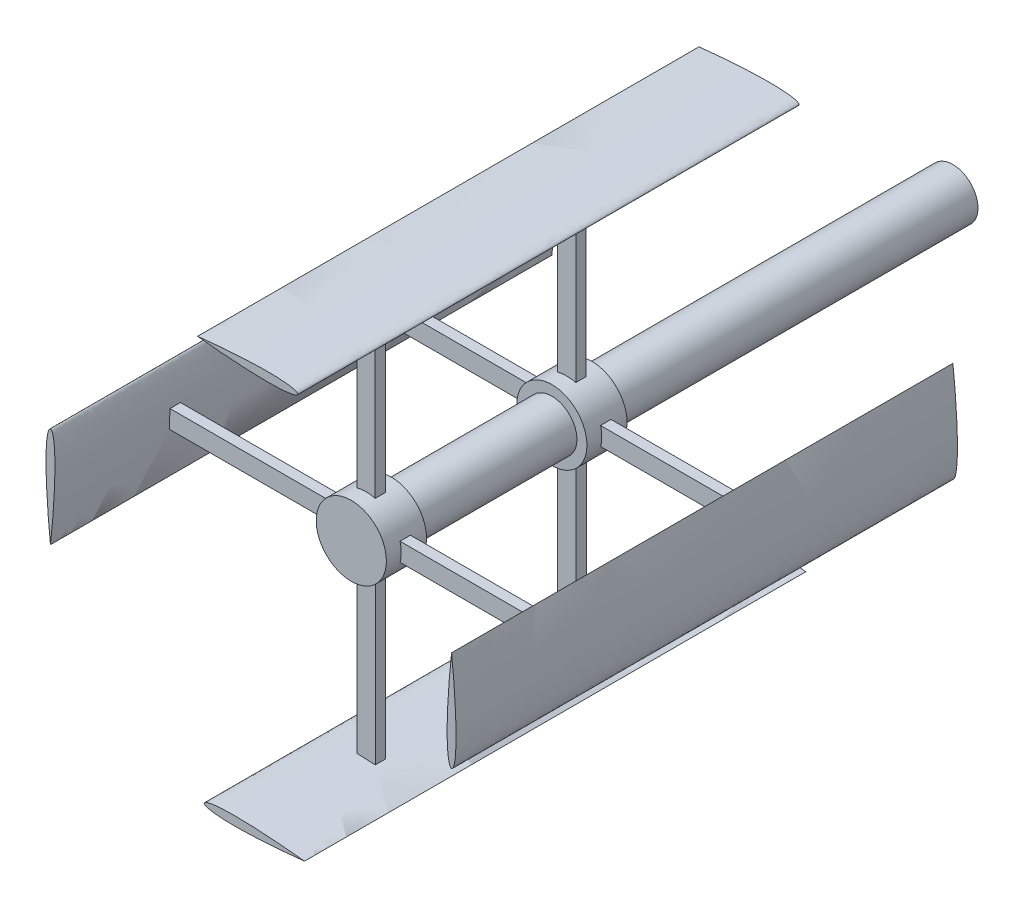
SolidWorks part; units mm, degrees
ref_plane "Front Plane" through (0, 0, 0) normal (0, 0, 1) x (1, 0, 0)
ref_plane "Top Plane" through (0, 0, 0) normal (0, 1, 0) x (1, 0, 0)
ref_plane "Right Plane" through (0, 0, 0) normal (1, 0, 0) x (0, 0, -1)
curve "Curve1"
  spline degree 3 poles (990.8652, -0.9511, 0) (1002.2959, 0, 0) (990.8652, 0.9511, 0) (981.4966, 2.5372, 0) (958.7395, 4.9688, 0) (930.7792, 7.9871, 0) (894.3471, 11.5291, 0) (851.5737, 15.4379, 0) (802.6464, 19.638, 0) (748.5888, 24.0066, 0) (690.2628, 28.3691, 0) (628.6855, 32.5963, 0) (564.9061, 36.4936, 0) (500.0164, 39.8961, 0) (435.1246, 42.6014, 0) (381.5433, 44.1643, 0) (339.5117, 44.8822, 0) (308.9339, 45.137, 0) (279.1721, 45.1014, 0) (250.3536, 44.7183, 0) (222.6042, 44.0458, 0) (196.0449, 43.0302, 0) (170.7873, 41.7085, 0) (146.9363, 40.0498, 0) (124.593, 38.0822, 0) (103.8602, 35.7885, 0) (84.8245, 33.2124, 0) (67.5602, 30.4204, 0) (52.1393, 27.4249, 0) (38.6118, 24.2363, 0) (27.0418, 20.7473, 0) (17.4544, 16.8931, 0) (9.9374, 12.6406, 0) (4.5317, 8.2, 0) (1.1558, 4.1301, 0) (-0.473, 0, 0) (1.1558, -4.1301, 0) (4.5317, -8.2, 0) (9.9374, -12.6406, 0) (17.4544, -16.8931, 0) (27.0418, -20.7473, 0) (38.6118, -24.2363, 0) (52.1393, -27.4249, 0) (67.5602, -30.4204, 0) (84.8245, -33.2124, 0) (103.8602, -35.7885, 0) (124.593, -38.0822, 0) (146.9363, -40.0498, 0) (170.7873, -41.7085, 0) (196.0449, -43.0302, 0) (222.6042, -44.0458, 0) (250.3536, -44.7183, 0) (279.1721, -45.1014, 0) (308.9339, -45.137, 0) (339.5117, -44.8822, 0) (381.5433, -44.1643, 0) (435.1246, -42.6014, 0) (500.0164, -39.8961, 0) (564.9061, -36.4936, 0) (628.6855, -32.5963, 0) (690.2628, -28.3691, 0) (748.5888, -24.0066, 0) (802.6464, -19.638, 0) (851.5737, -15.4379, 0) (894.3471, -11.5291, 0) (930.7792, -7.9871, 0) (958.7395, -4.9688, 0) (981.4966, -2.5372, 0) (990.8652, -0.9511, 0) (1002.2959, 0, 0) (990.8652, 0.9511, 0) knots -0.018944 -0.008488 -0.002133 0 0.002133 0.008488 0.018944 0.033319 0.051356 0.072756 0.097141 0.124097 0.153163 0.183834 0.215589 0.247878 0.280151 0.31186 0.327333 0.342463 0.357187 0.371448 0.385183 0.398331 0.410845 0.422673 0.433769 0.44409 0.453589 0.46224 0.47001 0.476871 0.482833 0.487909 0.492155 0.495592 0.498196 0.5 0.501804 0.504408 0.507845 0.512091 0.517167 0.523129 0.52999 0.53776 0.546411 0.55591 0.566231 0.577327 0.589155 0.601669 0.614817 0.628552 0.642813 0.657537 0.672667 0.68814 0.719849 0.752122 0.784411 0.816166 0.846837 0.875903 0.902859 0.927244 0.948644 0.966681 0.981056 0.991512 0.997867 1 1.002133 1.008488 1.018944 periodic
sketch "Sketch2" plane through (0, 0, 0) normal (0, 0, 1) x (1, 0, 0)
  line L0 (0, 0) -> (1000, 0)
  circle A0 centre (466.8967, 2000) radius 2000
  spline S0 degree 3 poles (990.8652, -0.9511) (1002.2959, 0) (990.8652, 0.9511) (981.4966, 2.5372) (958.7395, 4.9688) (930.7792, 7.9871) (894.3471, 11.5291) (851.5737, 15.4379) (802.6464, 19.638) (748.5888, 24.0066) (690.2628, 28.3691) (628.6855, 32.5963) (564.9061, 36.4936) (500.0164, 39.8961) (435.1246, 42.6014) (381.5433, 44.1643) (339.5117, 44.8822) (308.9339, 45.137) (279.1721, 45.1014) (250.3536, 44.7183) (222.6042, 44.0458) (196.0449, 43.0302) (170.7873, 41.7085) (146.9363, 40.0498) (124.593, 38.0822) (103.8602, 35.7885) (84.8245, 33.2124) (67.5602, 30.4204) (52.1393, 27.4249) (38.6118, 24.2363) (27.0418, 20.7473) (17.4544, 16.8931) (9.9374, 12.6406) (4.5317, 8.2) (1.1558, 4.1301) (-0.473, 0) (1.1558, -4.1301) (4.5317, -8.2) (9.9374, -12.6406) (17.4544, -16.8931) (27.0418, -20.7473) (38.6118, -24.2363) (52.1393, -27.4249) (67.5602, -30.4204) (84.8245, -33.2124) (103.8602, -35.7885) (124.593, -38.0822) (146.9363, -40.0498) (170.7873, -41.7085) (196.0449, -43.0302) (222.6042, -44.0458) (250.3536, -44.7183) (279.1721, -45.1014) (308.9339, -45.137) (339.5117, -44.8822) (381.5433, -44.1643) (435.1246, -42.6014) (500.0164, -39.8961) (564.9061, -36.4936) (628.6855, -32.5963) (690.2628, -28.3691) (748.5888, -24.0066) (802.6464, -19.638) (851.5737, -15.4379) (894.3471, -11.5291) (930.7792, -7.9871) (958.7395, -4.9688) (981.4966, -2.5372) (990.8652, -0.9511) (1002.2959, 0) (990.8652, 0.9511) knots -0.018944 -0.008488 -0.002133 0 0.002133 0.008488 0.018944 0.033319 0.051356 0.072756 0.097141 0.124097 0.153163 0.183834 0.215589 0.247878 0.280151 0.31186 0.327333 0.342463 0.357187 0.371448 0.385183 0.398331 0.410845 0.422673 0.433769 0.44409 0.453589 0.46224 0.47001 0.476871 0.482833 0.487909 0.492155 0.495592 0.498196 0.5 0.501804 0.504408 0.507845 0.512091 0.517167 0.523129 0.52999 0.53776 0.546411 0.55591 0.566231 0.577327 0.589155 0.601669 0.614817 0.628552 0.642813 0.657537 0.672667 0.68814 0.719849 0.752122 0.784411 0.816166 0.846837 0.875903 0.902859 0.927244 0.948644 0.966681 0.981056 0.991512 0.997867 1 1.002133 1.008488 1.018944 only from (1000, 0) to (1000, 0) construction
  dimension "D1" = 4000
sketch "Sketch3" plane through (0, 0, 0) normal (0, 1, 0) x (1, 0, 0)
  line L1 (500, 0) -> (500, -5000)
  line L2 (0, 0) -> (1000, 0) construction
  dimension "D1" = 5000
sketch "Sketch4" plane through (0, 0, 0) normal (0, 0, 1) x (1, 0, 0)
  spline S0 degree 3 poles (990.8652, -0.9511) (1002.2959, 0) (990.8652, 0.9511) (981.4966, 2.5372) (958.7395, 4.9688) (930.7792, 7.9871) (894.3471, 11.5291) (851.5737, 15.4379) (802.6464, 19.638) (748.5888, 24.0066) (690.2628, 28.3691) (628.6855, 32.5963) (564.9061, 36.4936) (500.0164, 39.8961) (435.1246, 42.6014) (381.5433, 44.1643) (339.5117, 44.8822) (308.9339, 45.137) (279.1721, 45.1014) (250.3536, 44.7183) (222.6042, 44.0458) (196.0449, 43.0302) (170.7873, 41.7085) (146.9363, 40.0498) (124.593, 38.0822) (103.8602, 35.7885) (84.8245, 33.2124) (67.5602, 30.4204) (52.1393, 27.4249) (38.6118, 24.2363) (27.0418, 20.7473) (17.4544, 16.8931) (9.9374, 12.6406) (4.5317, 8.2) (1.1558, 4.1301) (-0.473, 0) (1.1558, -4.1301) (4.5317, -8.2) (9.9374, -12.6406) (17.4544, -16.8931) (27.0418, -20.7473) (38.6118, -24.2363) (52.1393, -27.4249) (67.5602, -30.4204) (84.8245, -33.2124) (103.8602, -35.7885) (124.593, -38.0822) (146.9363, -40.0498) (170.7873, -41.7085) (196.0449, -43.0302) (222.6042, -44.0458) (250.3536, -44.7183) (279.1721, -45.1014) (308.9339, -45.137) (339.5117, -44.8822) (381.5433, -44.1643) (435.1246, -42.6014) (500.0164, -39.8961) (564.9061, -36.4936) (628.6855, -32.5963) (690.2628, -28.3691) (748.5888, -24.0066) (802.6464, -19.638) (851.5737, -15.4379) (894.3471, -11.5291) (930.7792, -7.9871) (958.7395, -4.9688) (981.4966, -2.5372) (990.8652, -0.9511) (1002.2959, 0) (990.8652, 0.9511) knots -0.018944 -0.008488 -0.002133 0 0.002133 0.008488 0.018944 0.033319 0.051356 0.072756 0.097141 0.124097 0.153163 0.183834 0.215589 0.247878 0.280151 0.31186 0.327333 0.342463 0.357187 0.371448 0.385183 0.398331 0.410845 0.422673 0.433769 0.44409 0.453589 0.46224 0.47001 0.476871 0.482833 0.487909 0.492155 0.495592 0.498196 0.5 0.501804 0.504408 0.507845 0.512091 0.517167 0.523129 0.52999 0.53776 0.546411 0.55591 0.566231 0.577327 0.589155 0.601669 0.614817 0.628552 0.642813 0.657537 0.672667 0.68814 0.719849 0.752122 0.784411 0.816166 0.846837 0.875903 0.902859 0.927244 0.948644 0.966681 0.981056 0.991512 0.997867 1 1.002133 1.008488 1.018944 only from (1000, 0) to (1000, 0) construction
  spline S1 degree 3 poles (990.8652, -0.9511) (1002.2959, 0) (990.8652, 0.9511) (981.4966, 2.5372) (958.7395, 4.9688) (930.7792, 7.9871) (894.3471, 11.5291) (851.5737, 15.4379) (802.6464, 19.638) (748.5888, 24.0066) (690.2628, 28.3691) (628.6855, 32.5963) (564.9061, 36.4936) (500.0164, 39.8961) (435.1246, 42.6014) (381.5433, 44.1643) (339.5117, 44.8822) (308.9339, 45.137) (279.1721, 45.1014) (250.3536, 44.7183) (222.6042, 44.0458) (196.0449, 43.0302) (170.7873, 41.7085) (146.9363, 40.0498) (124.593, 38.0822) (103.8602, 35.7885) (84.8245, 33.2124) (67.5602, 30.4204) (52.1393, 27.4249) (38.6118, 24.2363) (27.0418, 20.7473) (17.4544, 16.8931) (9.9374, 12.6406) (4.5317, 8.2) (1.1558, 4.1301) (-0.473, 0) (1.1558, -4.1301) (4.5317, -8.2) (9.9374, -12.6406) (17.4544, -16.8931) (27.0418, -20.7473) (38.6118, -24.2363) (52.1393, -27.4249) (67.5602, -30.4204) (84.8245, -33.2124) (103.8602, -35.7885) (124.593, -38.0822) (146.9363, -40.0498) (170.7873, -41.7085) (196.0449, -43.0302) (222.6042, -44.0458) (250.3536, -44.7183) (279.1721, -45.1014) (308.9339, -45.137) (339.5117, -44.8822) (381.5433, -44.1643) (435.1246, -42.6014) (500.0164, -39.8961) (564.9061, -36.4936) (628.6855, -32.5963) (690.2628, -28.3691) (748.5888, -24.0066) (802.6464, -19.638) (851.5737, -15.4379) (894.3471, -11.5291) (930.7792, -7.9871) (958.7395, -4.9688) (981.4966, -2.5372) (990.8652, -0.9511) (1002.2959, 0) (990.8652, 0.9511) knots -0.018944 -0.008488 -0.002133 0 0.002133 0.008488 0.018944 0.033319 0.051356 0.072756 0.097141 0.124097 0.153163 0.183834 0.215589 0.247878 0.280151 0.31186 0.327333 0.342463 0.357187 0.371448 0.385183 0.398331 0.410845 0.422673 0.433769 0.44409 0.453589 0.46224 0.47001 0.476871 0.482833 0.487909 0.492155 0.495592 0.498196 0.5 0.501804 0.504408 0.507845 0.512091 0.517167 0.523129 0.52999 0.53776 0.546411 0.55591 0.566231 0.577327 0.589155 0.601669 0.614817 0.628552 0.642813 0.657537 0.672667 0.68814 0.719849 0.752122 0.784411 0.816166 0.846837 0.875903 0.902859 0.927244 0.948644 0.966681 0.981056 0.991512 0.997867 1 1.002133 1.008488 1.018944 only from (1000, 0) to (1000, 0)
sweep "Sweep1" add profiles "Sketch4" path "Sketch3"
sketch "Sketch5" plane through (0, 0, 0) normal (0, 0, 1) x (1, 0, 0)
  circle A0 centre (466.8967, 2000) radius 250
extrude "Boss-Extrude1" add sketch "Sketch5" along normal blind 4000 and the other way blind 2000 separate body
pattern_circular "CirPattern1" count 4 over 360 about axis through (466.8967, 2000, -2000) along (0, 0, 1) of bodies 101
ref_plane "Plane1" through (0, 0, 4000) normal (0, 0, 1) x (1, 0, 0)
sketch "Sketch6" plane through (0, 0, 4000) normal (0, 0, 1) x (1, 0, 0)
  circle A0 centre (466.8967, 2000) radius 250
  circle A1 centre (466.8967, 2000) radius 350
  dimension "D1" = 700
extrude "Boss-Extrude2" add sketch "Sketch6" against normal blind 400
ref_plane "Plane2" through (0, 3000, 0) normal (0, 1, 0) x (1, 0, 0)
ref_plane "Plane3" through (0, 0, 3800) normal (0, 0, 1) x (1, 0, 0)
sketch "Sketch9" plane through (0, 3000, 0) normal (0, 1, 0) x (1, 0, 0)
  line L2 (375.5632, -3852.1745) -> (557.5355, -3852.1745)
  line L3 (375.5632, -3852.1745) -> (375.5632, -3747.8255)
  line L4 (375.5632, -3747.8255) -> (557.5355, -3747.8255)
  line L5 (557.5355, -3852.1745) -> (557.5355, -3747.8255)
  line L6 (375.5632, -3852.1745) -> (557.5355, -3747.8255) construction
  line L7 (375.5632, -3747.8255) -> (557.5355, -3852.1745) construction
extrude "Boss-Extrude4" add sketch "Sketch9" against normal up to surface and the other way blind 343 contours L2 L5 L4 L3 up to face at (816.8967, 2000, 3600)
pattern_circular "CirPattern3" count 4 over 360 about axis through (466.8967, 2000, 0) along (0, 0, 1) of "Boss-Extrude4"
sketch "Sketch10" plane through (0, 3343, 0) normal (0, 1, 0) x (1, 0, 0)
  line L1 (375.5632, -3747.8255) -> (557.5355, -3747.8255)
  line L2 (375.5632, -3747.8255) -> (375.5632, -3852.1745)
  line L3 (375.5632, -3852.1745) -> (557.5355, -3852.1745)
  line L4 (557.5355, -3747.8255) -> (557.5355, -3852.1745)
extrude "Boss-Extrude5" add sketch "Sketch10" along normal up to next
sketch "Sketch11" plane through (-876.1033, 0, 0) normal (-1, 0, 0) x (0, 0, 1)
  line L1 (3852.1745, 2090.6389) -> (3747.8255, 2090.6389)
  line L2 (3852.1745, 2090.6389) -> (3852.1745, 1908.6665)
  line L3 (3852.1745, 1908.6665) -> (3747.8255, 1908.6665)
  line L4 (3747.8255, 2090.6389) -> (3747.8255, 1908.6665)
extrude "Boss-Extrude6" add sketch "Sketch11" along normal up to next
sketch "Sketch13" plane through (0, 657, 0) normal (0, -1, 0) x (1, 0, 0)
  line L1 (558.2302, 3747.8255) -> (376.2578, 3747.8255)
  line L2 (558.2302, 3747.8255) -> (558.2302, 3852.1745)
  line L3 (558.2302, 3852.1745) -> (376.2578, 3852.1745)
  line L4 (376.2578, 3747.8255) -> (376.2578, 3852.1745)
extrude "Boss-Extrude7" add sketch "Sketch13" along normal up to next
sketch "Sketch14" plane through (1809.8967, 0, 0) normal (1, 0, 0) x (0, 0, -1)
  line L1 (-3852.1745, 1909.3611) -> (-3747.8255, 1909.3611)
  line L2 (-3852.1745, 1909.3611) -> (-3852.1745, 2091.3335)
  line L3 (-3852.1745, 2091.3335) -> (-3747.8255, 2091.3335)
  line L4 (-3747.8255, 1909.3611) -> (-3747.8255, 2091.3335)
extrude "Boss-Extrude8" add sketch "Sketch14" along normal up to next
pattern_linear "LPattern1" count 2 spacing 2000 along (0, 0, -1) of "Boss-Extrude8", "Boss-Extrude7", "Boss-Extrude5", "Boss-Extrude6", "Boss-Extrude4", "CirPattern3", "Boss-Extrude2"
